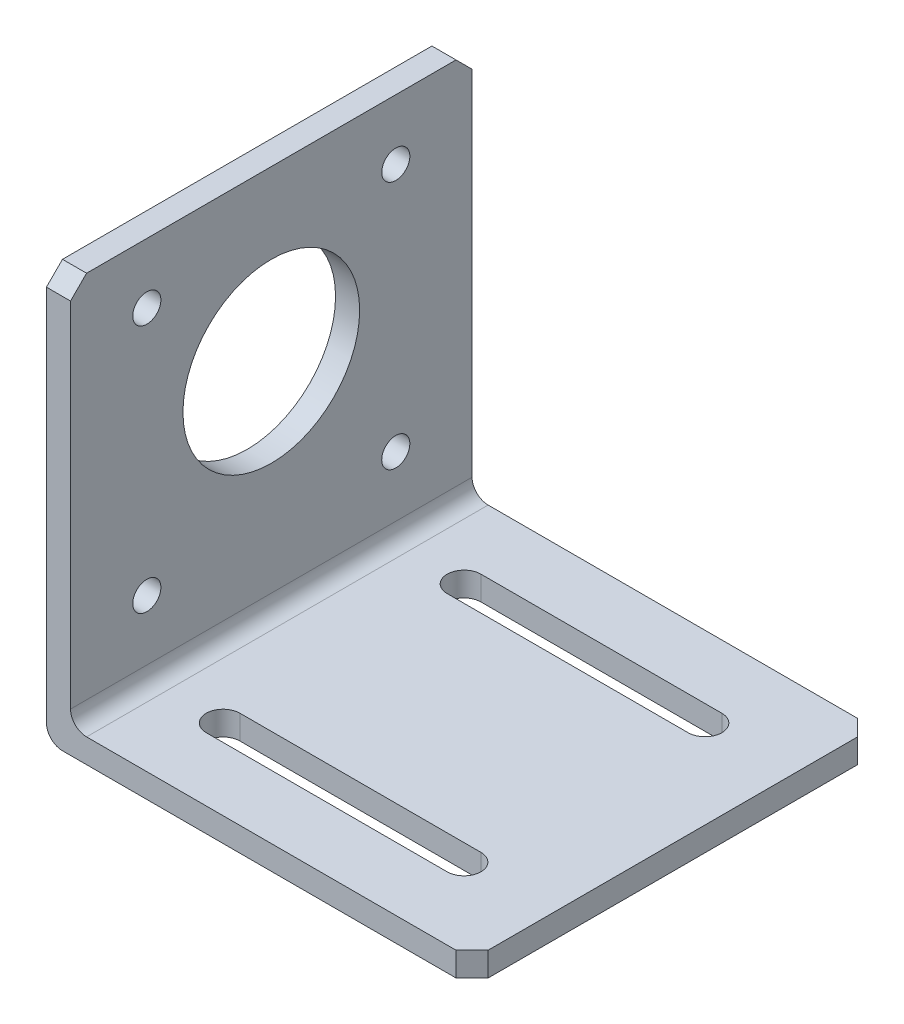
SolidWorks part; units mm, degrees
ref_plane "Ön Düzlem" through (0, 0, 0) normal (0, 0, 1) x (1, 0, 0)
ref_plane "Üst Düzlem" through (0, 0, 0) normal (0, 1, 0) x (1, 0, 0)
ref_plane "Sağ Düzlem" through (0, 0, 0) normal (1, 0, 0) x (0, 0, -1)
sketch "Çizim1" plane through (0, 0, 0) normal (0, 0, 1) x (1, 0, 0)
  line L0 (0, 51) -> (0, 2)
  line L1 (2, 0) -> (53, 0)
  line L2 (53, 0) -> (53, 3)
  line L3 (53, 3) -> (5, 3)
  line L4 (3, 5) -> (3, 51)
  line L5 (3, 51) -> (0, 51)
  arc A0 (5, 3) -> (3, 5) centre (5, 5) cw
  arc A1 (0, 2) -> (2, 0) centre (2, 2) ccw
  point P11 (0, 0)
  dimension "D2" = 2
  dimension "D5" = 2
  dimension "D1" = 3
  dimension "D3" = 51
  dimension "D4" = 53
extrude "Yükseklik-Ekstrüzyon1" add sketch "Çizim1" along normal blind 50
sketch "Çizim2" plane through (3, 0, 0) normal (1, 0, 0) x (0, 0, -1)
  circle A1 centre (-25, 30) radius 11
  circle A2 centre (-9.5, 43.5) radius 1.75
  circle A3 centre (-40.5, 43.5) radius 1.75
  circle A6 centre (-9.5, 12.5) radius 1.75
  circle A7 centre (-40.5, 12.5) radius 1.75
  dimension "D2" = 22
  dimension "D6" = 3.5
extrude "Kes-Ekstrüzyon1" cut sketch "Çizim2" against normal through all contours A3 | A1 | A2 | A7 | A6
sketch "Çizim3" plane through (0, 3, 0) normal (0, 1, 0) x (1, 0, 0)
  line L3 (42, -12.1) -> (12, -12.1)
  line L4 (42, -7.9) -> (12, -7.9)
  line L6 (42, -37.9) -> (12, -37.9)
  line L7 (42, -42.1) -> (12, -42.1)
  arc A0 (42, -12.1) -> (42, -7.9) centre (42, -10) ccw
  arc A1 (12, -7.9) -> (12, -12.1) centre (12, -10) ccw
  arc A2 (12, -42.1) -> (12, -37.9) centre (12, -40) cw
  arc A3 (42, -37.9) -> (42, -42.1) centre (42, -40) cw
  dimension "D3" = 4.2
  dimension "D4" = 30
extrude "Kes-Ekstrüzyon2" cut sketch "Çizim3" against normal blind 10 and the other way through all contours L6 A2 L7 A3 | A0 L4 A1 L3
sketch "Çizim4" plane through (3, 0, 0) normal (1, 0, 0) x (0, 0, -1)
  line L0 (-50, 49) -> (-50, 51)
  line L1 (-50, 49) -> (-48, 51)
  line L3 (-50, 51) -> (-48, 51)
  line L5 (0, 49) -> (0, 51)
  line L6 (0, 49) -> (-2, 51)
  line L7 (0, 51) -> (-2, 51)
  point P0 (-50, 51)
  dimension "D1" = 2
extrude "Kes-Ekstrüzyon3" cut sketch "Çizim4" against normal through all contours L7 L6 L5 | L3 L1 L0
sketch "Çizim5" plane through (0, 3, 0) normal (0, 1, 0) x (1, 0, 0)
  line L4 (53, -48) -> (51, -50)
  line L5 (51, -50) -> (53, -50)
  line L6 (53, -50) -> (53, -48)
  line L7 (53, 0) -> (53, -2)
  line L8 (51, 0) -> (53, 0)
  line L9 (53, -2) -> (51, 0)
  point P0 (53, -50)
  point P12 (53, 0)
  dimension "D1" = 2
extrude "Kes-Ekstrüzyon4" cut sketch "Çizim5" against normal through all contours L5 L6 L4 | L7 L9 L8
